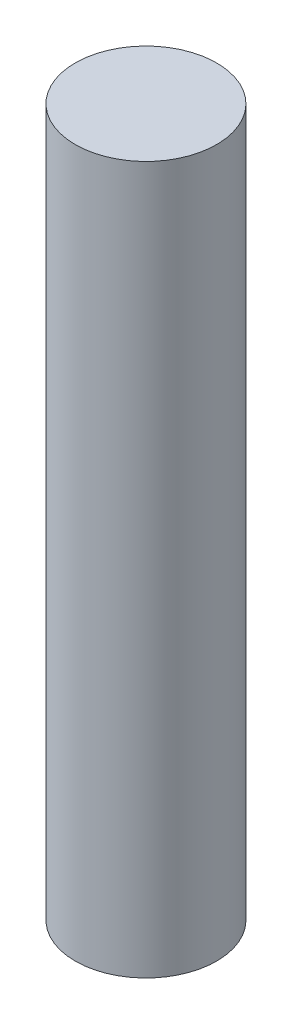
SolidWorks part; units mm, degrees
ref_plane "Front Plane" through (0, 0, 0) normal (0, 0, 1) x (1, 0, 0)
ref_plane "Top Plane" through (0, 0, 0) normal (0, 1, 0) x (1, 0, 0)
ref_plane "Right Plane" through (0, 0, 0) normal (1, 0, 0) x (0, 0, -1)
sketch "Sketch1" plane through (0, 0, 0) normal (0, 1, 0) x (1, 0, 0)
  circle A0 centre (0, 0) radius 1
  dimension "D1" = 2
extrude "Boss-Extrude1" add sketch "Sketch1" along normal blind 10
